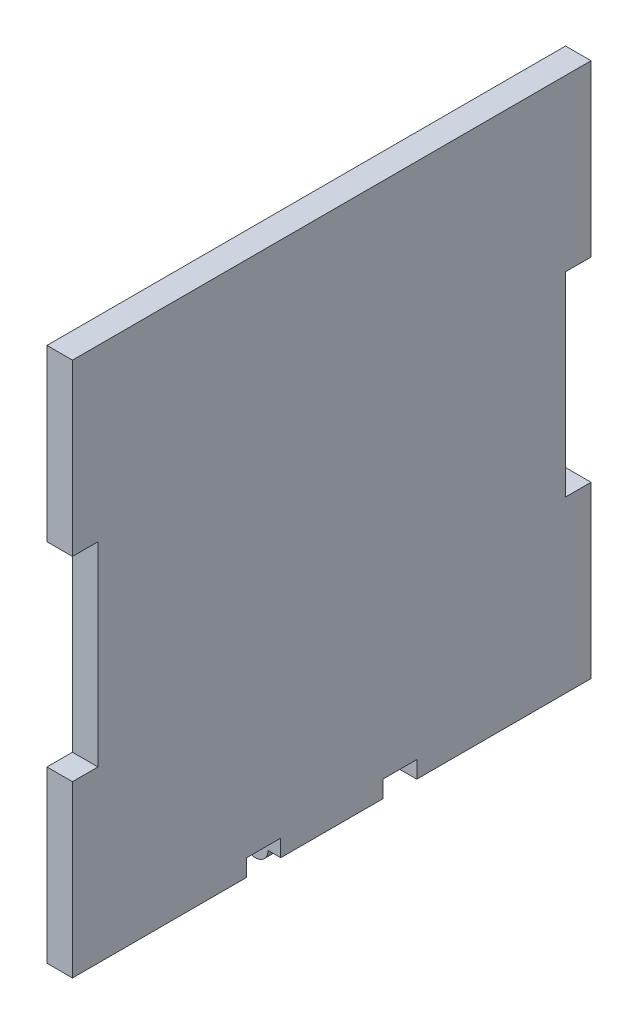
SolidWorks part; units mm, degrees
material "Acrilico TEC"
ref_plane "Front Plane" through (0, 0, 0) normal (0, 0, 1) x (1, 0, 0)
ref_plane "Top Plane" through (0, 0, 0) normal (0, 1, 0) x (1, 0, 0)
ref_plane "Right Plane" through (0, 0, 0) normal (1, 0, 0) x (0, 0, -1)
sketch "Sketch1" plane through (0, 0, 0) normal (1, 0, 0) x (0, 0, -1)
  line L0 (-27.5, 0) -> (27.5, 0)
  line L1 (-30.5, 42.94) -> (-30.5, 62.94)
  line L2 (27.5, 20) -> (30.5, 20)
  line L3 (-27.5, 20) -> (-27.5, 42.94)
  line L4 (30.5, 42.94) -> (27.5, 42.94)
  line L5 (-30.5, 0) -> (-30.5, 20)
  line L6 (27.5, 62.94) -> (-27.5, 62.94)
  line L7 (0, 62.94) -> (0, 0) construction
  line L8 (-30.5, 42.94) -> (-27.5, 42.94)
  line L9 (-27.5, 20) -> (-30.5, 20)
  line L10 (-30.5, 62.94) -> (-27.5, 62.94)
  line L11 (-30.5, 0) -> (-27.5, 0)
  line L13 (27.5, 0) -> (30.5, 0)
  line L14 (30.5, 0) -> (30.5, 20)
  line L15 (27.5, 20) -> (27.5, 42.94)
  line L16 (30.5, 42.94) -> (30.5, 62.94)
  line L17 (30.5, 62.94) -> (27.5, 62.94)
  dimension "D1" = 27.5
  dimension "D2" = 20
  dimension "D3" = 3
  dimension "D4" = 20
  dimension "D5" = 22.94
extrude "Boss-Extrude1" add sketch "Sketch1" along normal blind 3
ref_plane "Plane1" through (0, 0, 3) normal (0, 0, 1) x (1, 0, 0)
sketch "Sketch4" plane through (0, 0, 3) normal (0, 0, 1) x (1, 0, 0)
  circle A0 centre (0, 0) radius 1.5
  dimension "D1" = 3
extrude "Boss-Extrude2" add sketch "Sketch4" along normal blind 3
sketch "Sketch5" plane through (0, 0, 0) normal (-1, 0, 0) x (0, 0, 1)
  line L0 (6, 0) -> (-18, 0) construction
  line L1 (-10, 0) -> (-6, 0)
  line L2 (-10, 0) -> (-10, 2)
  line L3 (-10, 2) -> (-6, 2)
  line L4 (-6, 0) -> (-6, 2)
  line L5 (0, 0) -> (0, 14.9587) construction
  line L6 (6, 0) -> (6, 2)
  line L7 (10, 2) -> (6, 2)
  line L8 (10, 0) -> (10, 2)
  line L9 (10, 0) -> (6, 0)
  dimension "D1" = 4
  dimension "D2" = 2
  dimension "D3" = 6
extrude "Cut-Extrude1" cut sketch "Sketch5" against normal blind 10
pattern_linear "LPattern1" count 2 spacing 9 along (0, 0, -1) of "Boss-Extrude2"
